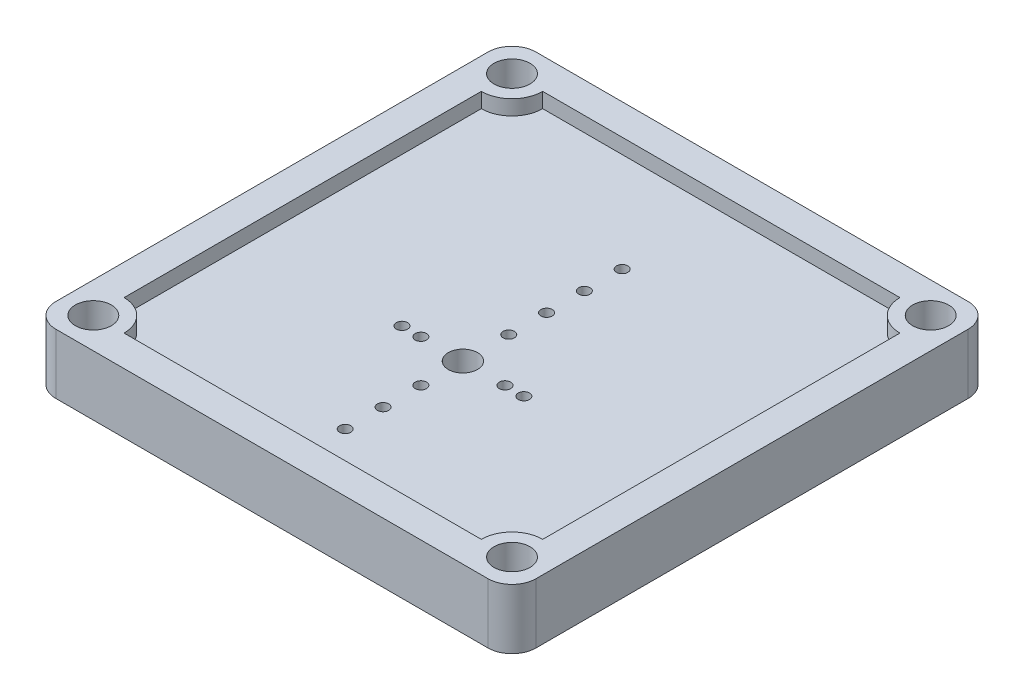
SolidWorks part; units mm, degrees
material "ABS PC"
ref_plane "Front Plane" through (0, 0, 0) normal (0, 0, 1) x (1, 0, 0)
ref_plane "Top Plane" through (0, 0, 0) normal (0, 1, 0) x (1, 0, 0)
ref_plane "Right Plane" through (0, 0, 0) normal (1, 0, 0) x (0, 0, -1)
sketch "Sketch1" plane through (0, 0, 0) normal (0, 1, 0) x (1, 0, 0)
  line L0 (0, 50.8) -> (3.2513, 47.5487)
  line L1 (0, 0) -> (50.8, 0)
  line L2 (0, 0) -> (0, 50.8)
  line L3 (0, 50.8) -> (50.8, 50.8)
  line L4 (50.8, 0) -> (50.8, 50.8)
  line L5 (0, 25.4) -> (50.8, 25.4) construction
  line L6 (25.4, 50.8) -> (25.4, 0) construction
  circle A0 centre (3.2513, 47.5487) radius 1.905
  circle A1 centre (3.2513, 3.2513) radius 1.905
  circle A2 centre (47.5487, 3.2513) radius 1.905
  circle A3 centre (47.5487, 47.5487) radius 1.905
  circle A4 centre (25.404, 11.752) radius 0.6 construction
  circle A5 centre (18.954, 20.202) radius 0.6 construction
  circle A6 centre (20.954, 20.202) radius 0.6 construction
  circle A7 centre (31.854, 20.202) radius 0.6 construction
  circle A8 centre (29.854, 20.202) radius 0.6 construction
  circle A9 centre (25.404, 37.052) radius 0.6 construction
  circle A10 centre (25.404, 33.052) radius 0.6 construction
  circle A11 centre (25.404, 29.052) radius 0.6 construction
  circle A12 centre (25.404, 25.052) radius 0.6 construction
  circle A13 centre (25.404, 7.752) radius 0.6 construction
  circle A14 centre (25.404, 15.752) radius 0.6 construction
  circle A15 centre (25.404, 20.202) radius 1.55 construction
  circle A16 centre (25.404, 11.752) radius 0.6
  circle A17 centre (18.954, 20.202) radius 0.6
  circle A18 centre (20.954, 20.202) radius 0.6
  circle A19 centre (31.854, 20.202) radius 0.6
  circle A20 centre (29.854, 20.202) radius 0.6
  circle A21 centre (25.404, 37.052) radius 0.6
  circle A22 centre (25.404, 33.052) radius 0.6
  circle A23 centre (25.404, 29.052) radius 0.6
  circle A24 centre (25.404, 25.052) radius 0.6
  circle A25 centre (25.404, 7.752) radius 0.6
  circle A26 centre (25.404, 15.752) radius 0.6
  circle A27 centre (25.404, 20.202) radius 1.55
  dimension "D1" = 3.81
  dimension "D2" = 50.8
  dimension "D3" = 50.8
extrude "Boss-Extrude1" add sketch "Sketch1" along normal blind 6.35
sketch "Sketch2" plane through (0, 0, 0) normal (0, 1, 0) x (1, 0, 0)
  line L0 (3.2513, 44.2975) -> (3.2513, 6.5025)
  line L1 (6.5025, 3.2513) -> (44.2975, 3.2513)
  line L2 (47.5487, 44.2975) -> (47.5487, 6.5025)
  line L3 (44.2975, 47.5487) -> (6.5025, 47.5487)
  circle A0 centre (3.2513, 47.5487) radius 1.905
  circle A1 centre (3.2513, 47.5487) radius 3.2513
  circle A2 centre (47.5487, 47.5487) radius 1.905
  circle A3 centre (47.5487, 47.5487) radius 3.2513
  circle A4 centre (47.5487, 3.2513) radius 1.905
  circle A5 centre (47.5487, 3.2513) radius 3.2513
  circle A6 centre (3.2513, 3.2513) radius 1.905
  circle A7 centre (3.2513, 3.2513) radius 3.2513
extrude "Cut-Extrude1" cut sketch "Sketch2" along normal blind 1.5875 from surface at 0 contours A7 L1 A5 L2 A3 L3 A1 L0 starting at face at (3.2513, 0, -45.6437)
sketch "Sketch3" plane through (0, 0, 0) normal (0, 1, 0) x (1, 0, 0)
  line L0 (3.2513, 44.2975) -> (3.2513, 6.5025)
  line L1 (6.5025, 3.2513) -> (44.2975, 3.2513)
  line L2 (47.5487, 44.2975) -> (47.5487, 6.5025)
  line L3 (44.2975, 47.5487) -> (6.5025, 47.5487)
  circle A0 centre (3.2513, 47.5487) radius 1.905
  circle A1 centre (3.2513, 47.5487) radius 3.2513
  circle A2 centre (47.5487, 47.5487) radius 1.905
  circle A3 centre (47.5487, 47.5487) radius 3.2513
  circle A4 centre (47.5487, 3.2513) radius 1.905
  circle A5 centre (47.5487, 3.2513) radius 3.2513
  circle A6 centre (3.2513, 3.2513) radius 1.905
  circle A7 centre (3.2513, 3.2513) radius 3.2513
extrude "Cut-Extrude2" cut sketch "Sketch3" against normal blind 1.5875 from surface at 6.35 contours A7 L1 A5 L2 A3 L3 A1 L0 starting at face at (3.2513, 6.35, -45.6437)
fillet "Fillet1" radius 2.54 4 edges at (50.8, 3.175, -50.8) (50.8, 3.175, 0) (0, 3.175, 0) (0, 3.175, -50.8)
